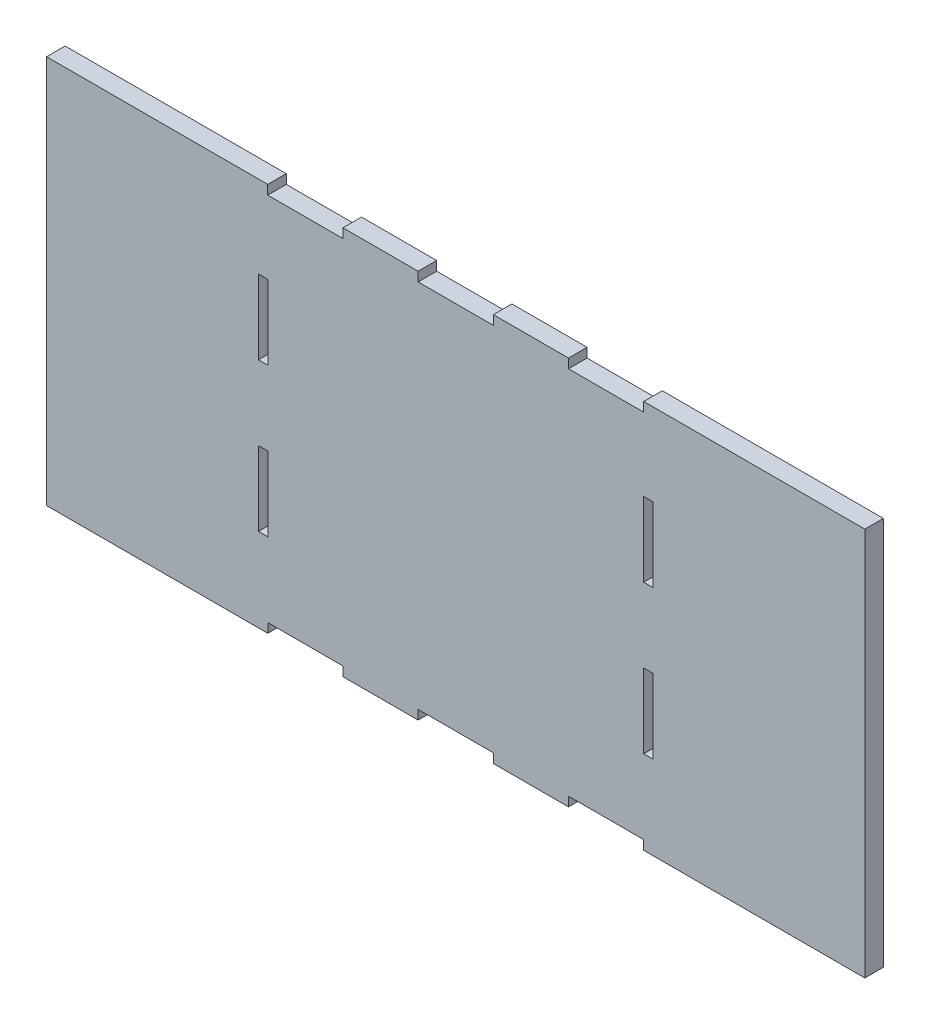
SolidWorks part; units mm, degrees
material "A-Glass Fiber"
ref_plane "Front Plane" through (0, 0, 0) normal (0, 0, 1) x (1, 0, 0)
ref_plane "Top Plane" through (0, 0, 0) normal (0, 1, 0) x (1, 0, 0)
ref_plane "Right Plane" through (0, 0, 0) normal (1, 0, 0) x (0, 0, -1)
sketch "Sketch1" plane through (0, 0, 0) normal (0, 0, 1) x (1, 0, 0)
  line L0 (0, 0) -> (1345.4471, 0)
  line L1 (212.2829, -469.9) -> (1133.1642, -469.9)
  line L2 (0, 0) -> (188.5098, -454.2888)
  line L3 (1345.4471, 0) -> (1156.9372, -454.2888)
  spline S1 degree 3 poles (1156.9372, -454.2888) (1155.9652, -456.6313) (1154.631, -458.8169) (1152.2259, -461.6935) (1151.3551, -462.5908) (1149.4733, -464.2609) (1148.4599, -465.0331) (1146.3603, -466.4012) (1145.2664, -467.0047) (1142.9909, -468.0521) (1141.799, -468.4985) (1138.1745, -469.5606) (1135.6993, -469.9116) (1133.1642, -469.9) knots 0 0 0 0 0.25 0.25 0.375 0.375 0.5 0.5 0.625 0.625 0.75 0.75 1 1 1 1
  spline S2 degree 3 poles (188.5098, -454.2888) (189.4819, -456.6313) (190.8161, -458.8169) (193.2211, -461.6935) (194.092, -462.5908) (195.9737, -464.2609) (196.9872, -465.0331) (199.0868, -466.4012) (200.1807, -467.0047) (202.4562, -468.0521) (203.6481, -468.4985) (207.2726, -469.5606) (209.7478, -469.9116) (212.2829, -469.9) knots 0 0 0 0 0.25 0.25 0.375 0.375 0.5 0.5 0.625 0.625 0.75 0.75 1 1 1 1
  dimension "D1" = 112.536
  dimension "D2" = 112.536
  dimension "D3" = 920.8813
  dimension "D4" = 469.9
extrude "Boss-Extrude1" add sketch "Sketch1" along normal blind 20.32
ref_plane "Plane1" through (672.7235, 0, 0) normal (1, 0, 0) x (0, 0, -1)
sketch "Sketch2" plane through (0, 0, 20.32) normal (0, 0, 1) x (1, 0, 0)
  line L0 (467.0082, -378.4231) -> (467.0082, -297.1061) construction
  line L1 (467.0082, -297.1061) -> (456.8417, -297.1061) construction
  line L2 (456.8417, -297.1061) -> (456.8417, -378.4231) construction
  line L3 (456.8417, -378.4231) -> (467.0082, -378.4231) construction
  line L4 (878.4388, -297.1061) -> (878.4388, -378.4231) construction
  line L5 (878.4388, -378.4231) -> (888.6053, -378.4231) construction
  line L6 (888.6053, -378.4231) -> (888.6053, -297.1061) construction
  line L7 (888.6053, -297.1061) -> (878.4388, -297.1061) construction
  line L8 (878.4388, -134.4722) -> (878.4388, -215.7892) construction
  line L9 (878.4388, -215.7892) -> (888.6053, -215.7892) construction
  line L10 (888.6053, -215.7892) -> (888.6053, -134.4722) construction
  line L11 (888.6053, -134.4722) -> (878.4388, -134.4722) construction
  line L24 (467.0082, -215.7892) -> (467.0082, -134.4722) construction
  line L25 (467.0082, -134.4722) -> (456.8417, -134.4722) construction
  line L26 (456.8417, -134.4722) -> (456.8417, -215.7892) construction
  line L27 (456.8417, -215.7892) -> (467.0082, -215.7892) construction
  line L28 (878.4388, -469.9) -> (878.4388, -459.74) construction
  line L29 (878.4388, -459.74) -> (796.1675, -459.74) construction
  line L30 (796.1675, -469.9) -> (796.1675, -459.74) construction
  line L31 (713.8592, -469.9) -> (713.8592, -459.74) construction
  line L32 (631.5879, -459.74) -> (713.8592, -459.74) construction
  line L33 (631.5879, -469.9) -> (631.5879, -459.74) construction
  line L34 (467.0082, -469.9) -> (467.0082, -459.74) construction
  line L35 (549.2795, -469.9) -> (549.2795, -459.74) construction
  line L36 (467.0082, -459.74) -> (549.2795, -459.74) construction
  line L37 (467.0082, -378.4231) -> (467.0082, -297.1061)
  line L38 (467.0082, -297.1061) -> (456.8417, -297.1061)
  line L39 (456.8417, -297.1061) -> (456.8417, -378.4231)
  line L40 (456.8417, -378.4231) -> (467.0082, -378.4231)
  line L41 (878.4388, -297.1061) -> (878.4388, -378.4231)
  line L42 (878.4388, -378.4231) -> (888.6053, -378.4231)
  line L43 (888.6053, -378.4231) -> (888.6053, -297.1061)
  line L44 (888.6053, -297.1061) -> (878.4388, -297.1061)
  line L45 (878.4388, -134.4722) -> (878.4388, -215.7892)
  line L46 (878.4388, -215.7892) -> (888.6053, -215.7892)
  line L47 (888.6053, -215.7892) -> (888.6053, -134.4722)
  line L48 (888.6053, -134.4722) -> (878.4388, -134.4722)
  line L61 (467.0082, -215.7892) -> (467.0082, -134.4722)
  line L62 (467.0082, -134.4722) -> (456.8417, -134.4722)
  line L63 (456.8417, -134.4722) -> (456.8417, -215.7892)
  line L64 (456.8417, -215.7892) -> (467.0082, -215.7892)
  line L65 (878.4388, -469.9) -> (878.4388, -459.74)
  line L66 (878.4388, -459.74) -> (796.1675, -459.74)
  line L67 (796.1675, -469.9) -> (796.1675, -459.74)
  line L68 (713.8592, -469.9) -> (713.8592, -459.74)
  line L69 (631.5879, -459.74) -> (713.8592, -459.74)
  line L70 (631.5879, -469.9) -> (631.5879, -459.74)
  line L71 (467.0082, -469.9) -> (467.0082, -459.74)
  line L72 (549.2795, -469.9) -> (549.2795, -459.74)
  line L73 (467.0082, -459.74) -> (549.2795, -459.74)
  line L74 (467.0082, -469.9) -> (549.2795, -469.9)
  line L75 (631.5879, -469.9) -> (713.8592, -469.9)
  line L76 (796.1675, -469.9) -> (878.4388, -469.9)
extrude "Cut-Extrude2" cut sketch "Sketch2" against normal blind 137.414
sketch "Sketch4" plane through (0, 0, 20.32) normal (0, 0, 1) x (1, 0, 0)
  line L0 (0, 0) -> (1345.4471, 0)
  line L1 (1345.4471, 0) -> (1327.0023, -44.45)
  line L2 (1156.9372, -454.2888) -> (1345.4471, 0) construction
  line L3 (1327.0023, -44.45) -> (18.4448, -44.45)
  line L4 (0, 0) -> (188.5098, -454.2888) construction
  line L5 (18.4448, -44.45) -> (0, 0)
  dimension "D1" = 44.45
extrude "Cut-Extrude3" cut sketch "Sketch4" against normal through all
sketch "Sketch5" plane through (0, 0, 20.32) normal (0, 0, 1) x (1, 0, 0)
  line L0 (672.7235, -11.176) -> (672.7235, 11.176) construction
  line L1 (713.8715, -54.61) -> (631.5755, -54.61)
  line L2 (713.8715, -54.61) -> (713.8715, -44.45)
  line L3 (713.8715, -44.45) -> (631.5755, -44.45)
  line L4 (631.5755, -54.61) -> (631.5755, -44.45)
  line L5 (713.8715, -54.61) -> (631.5755, -44.45) construction
  line L6 (713.8715, -44.45) -> (631.5755, -54.61) construction
  line L7 (18.4448, -44.45) -> (1327.0023, -44.45) construction
  line L9 (631.5755, -44.45) -> (549.2795, -44.45)
  line L10 (631.5755, -44.45) -> (631.5755, -54.61)
  line L11 (631.5755, -54.61) -> (549.2795, -54.61)
  line L12 (549.2795, -44.45) -> (549.2795, -54.61)
  line L13 (549.2795, -44.45) -> (466.9835, -44.45)
  line L14 (549.2795, -44.45) -> (549.2795, -54.61)
  line L15 (549.2795, -54.61) -> (466.9835, -54.61)
  line L16 (466.9835, -44.45) -> (466.9835, -54.61)
  line L17 (713.8715, -44.45) -> (796.1675, -44.45)
  line L18 (713.8715, -44.45) -> (713.8715, -54.61)
  line L19 (713.8715, -54.61) -> (796.1675, -54.61)
  line L20 (796.1675, -44.45) -> (796.1675, -54.61)
  line L21 (796.1675, -44.45) -> (878.4635, -44.45)
  line L22 (796.1675, -44.45) -> (796.1675, -54.61)
  line L23 (796.1675, -54.61) -> (878.4635, -54.61)
  line L24 (878.4635, -44.45) -> (878.4635, -54.61)
  point P0 (672.7235, -49.53)
  line M26 (1327.0023, -44.45) -> (18.4448, -44.45)
  dimension "D1" = 82.296
  dimension "D2" = 10.16
extrude "Cut-Extrude4" cut sketch "Sketch5" against normal through all contours L16 L15 L12 M26 | L4 L1 L2 M26 | L24 L20 L23 M26
sketch "Sketch6" plane through (0, 0, 20.32) normal (0, 0, 1) x (1, 0, 0)
  line L0 (192.8075, -448.0779) -> (224.9829, -469.9)
  line L2 (212.2829, -469.9) -> (467.0082, -469.9) construction
  line L4 (56.5448, -44.45) -> (56.5448, -119.699)
  line L5 (24.3099, -42.0162) -> (194.3749, -451.8551)
  line L6 (56.5448, -119.699) -> (192.8075, -448.0779)
  line L7 (18.4448, -44.45) -> (466.9835, -44.45) construction
  line L9 (56.5448, -44.45) -> (-120.2389, 37.3825)
  line L10 (-120.2389, 37.3825) -> (-59.5107, -242.3351)
  line L11 (-59.5107, -242.3351) -> (232.0802, -549.7664)
  line L12 (224.9829, -469.9) -> (232.0802, -549.7664)
  line L13 (672.7235, -54.61) -> (672.7235, -459.74) construction
  line L14 (713.8715, -54.61) -> (631.5755, -54.61) construction
  line L15 (713.8592, -459.74) -> (631.5879, -459.74) construction
  line L16 (1120.4642, -469.9) -> (1113.3668, -549.7664)
  line L17 (1404.9578, -242.3351) -> (1113.3668, -549.7664)
  line L18 (1465.686, 37.3825) -> (1404.9578, -242.3351)
  line L19 (1288.9023, -44.45) -> (1465.686, 37.3825)
  line L20 (1288.9023, -119.699) -> (1152.6395, -448.0779)
  line L21 (1288.9023, -44.45) -> (1288.9023, -119.699)
  line L22 (1152.6395, -448.0779) -> (1120.4642, -469.9)
  dimension "D1" = 12.7
  dimension "D2" = 38.1
  dimension "D3" = 6.35
extrude "Cut-Extrude5" cut sketch "Sketch6" against normal through all
sketch "Sketch7" plane through (0, 0, 20.32) normal (0, 0, 1) x (1, 0, 0)
  line L1 (224.9829, -469.9) -> (-145.5373, -469.9)
  line L2 (224.9829, -469.9) -> (224.9829, 127.8863)
  line L3 (224.9829, 127.8863) -> (-145.5373, 127.8863)
  line L4 (-145.5373, -469.9) -> (-145.5373, 127.8863)
  line L5 (1120.4642, -469.9) -> (1351.8588, -469.9)
  line L6 (1120.4642, -469.9) -> (1120.4642, 23.6984)
  line L7 (1120.4642, 23.6984) -> (1351.8588, 23.6984)
  line L8 (1351.8588, -469.9) -> (1351.8588, 23.6984)
extrude "Cut-Extrude6" cut sketch "Sketch7" against normal blind 25.4
